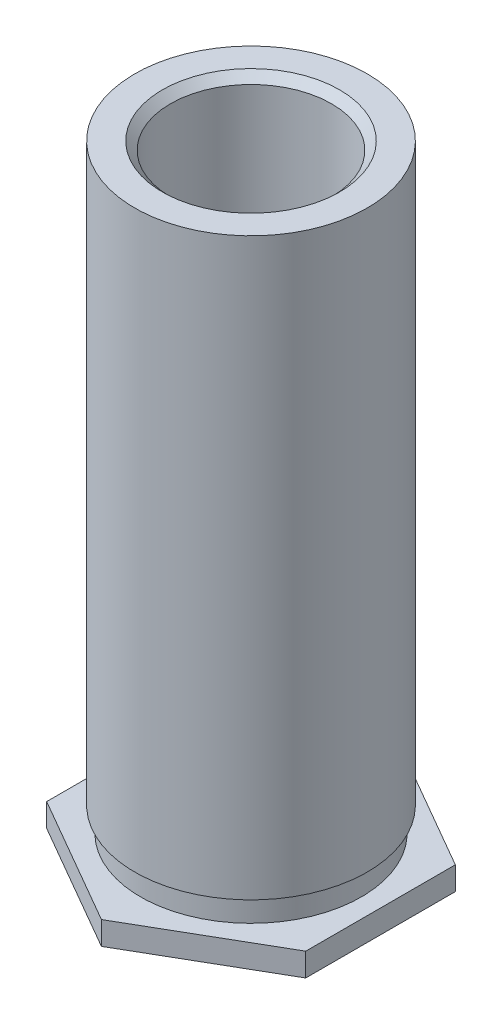
SolidWorks part; units mm, degrees
ref_plane "Plane1" through (0, 0, 0) normal (0, 0, 1) x (1, 0, 0)
ref_plane "Plane2" through (0, 0, 0) normal (0, 1, 0) x (1, 0, 0)
ref_plane "Plane3" through (0, 0, 0) normal (1, 0, 0) x (0, 0, -1)
sketch "BodySke" plane through (0, 0, 0) normal (0, 0, 1) x (1, 0, 0)
  line L0 (3.556, 0) -> (4.5964, 0)
  line L1 (4.5964, 0) -> (4.5964, 0.7112)
  line L2 (4.5964, 0.7112) -> (3.3782, 0.7112)
  line L3 (2.4638, 18.8036) -> (2.4638, 0.2515)
  line L4 (3.556, 1.458) -> (3.3782, 1.458)
  line L5 (3.3782, 1.458) -> (3.3782, 0.7112)
  line L6 (3.556, 0.0051) -> (3.556, 0)
  line L7 (2.7102, 0.0051) -> (3.556, 0.0051)
  line L8 (3.556, 19.05) -> (2.7102, 19.05)
  line L9 (0, 0) -> (0, 15.24) construction
  line L10 (2.7102, 19.05) -> (2.4638, 18.8036)
  line L11 (3.556, 19.05) -> (3.556, 1.458)
  line L12 (2.4638, 0.2515) -> (2.7102, 0.0051)
  dimension "E_dia" = 9.1928
  dimension "C_dia" = 7.112
  dimension "Length" = 19.05
  dimension "Clinching_ht" = 0.7112
  dimension "Groove_wid" = 0.7468
  dimension "Groove_dia" = 6.7564
  dimension "Thru_dia" = 4.9276
  dimension "D1" = 0.0051
  dimension "D2" = 45
  dimension "D3" = 45
  dimension "Chamfer_dia" = 5.4204
revolve "Body" add sketch "BodySke" angle 360 about L9
ref_plane "Plane4" through (0, -0.5486, 0) normal (0, 1, 0) x (-1, 0, 0)
sketch "HexDieSke" plane through (0, 0.7112, 0) normal (0, 1, 0) x (-1, 0, 0)
  line L0 (0, 4.5754) -> (3.9624, 2.2877)
  line L1 (3.9624, 2.2877) -> (3.9624, -2.2877)
  line L2 (3.9624, -2.2877) -> (0, -4.5754)
  line L3 (0, -4.5754) -> (-3.9624, -2.2877)
  line L4 (-3.9624, -2.2877) -> (-3.9624, 2.2877)
  line L5 (-3.9624, 2.2877) -> (0, 4.5754)
  circle A1 centre (0, 0) radius 3.9624 construction
  circle A2 centre (0, 0) radius 4.5754 construction
  circle A3 centre (0, 0) radius 4.6091
  dimension "Width_across_flats" = 7.9248
  dimension "OD" = 9.2182
extrude "HexDie" cut sketch "HexDieSke" against normal blind 0.7112
equation "' \"Length@BodySke\" = 0.75"
equation "' \"Thru_dia@BodySke\" = 0.194"
equation "' \"C_dia@BodySke\" = 0.28"
equation "' \"Width_across_flats@HexDieSke\" = 0.312"
equation "\"E_dia@BodySke\" = \"Width_across_flats@HexDieSke\" * 1.16"
equation "\"Chamfer_dia@BodySke\" = \"Thru_dia@BodySke\" * 1.1"
equation "\"Clinching_ht@BodySke\" = \"C_dia@BodySke\" * 0.1"
equation "\"Groove_dia@BodySke\" = \"C_dia@BodySke\" * 0.95"
equation "\"Groove_wid@BodySke\" = \"Clinching_ht@BodySke\" * 1.05"
equation "\"Depth@HexDie\" = \"Clinching_ht@BodySke\""
equation "\"OD@HexDieSke\" =  \"Width_across_flats@HexDieSke\" * 1.16 + 0.001"
